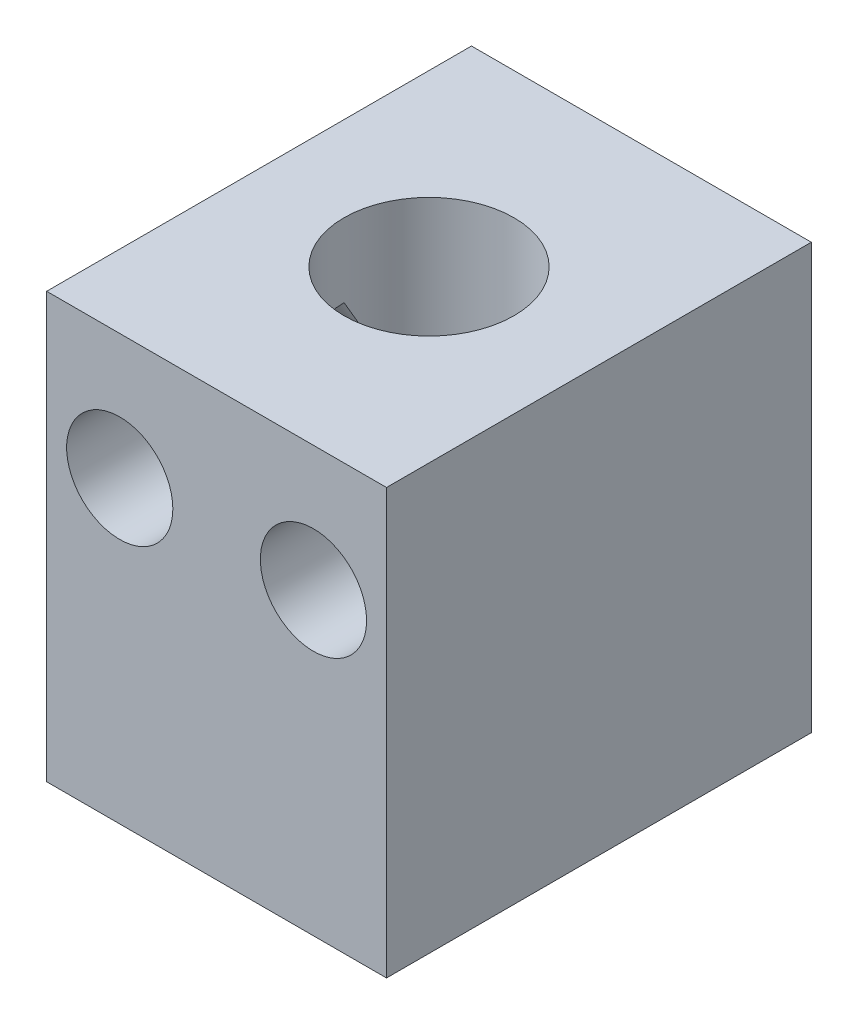
SolidWorks part; units mm, degrees
ref_plane "Plan de face" through (0, 0, 0) normal (0, 0, 1) x (1, 0, 0)
ref_plane "Plan de dessus" through (0, 0, 0) normal (0, 1, 0) x (1, 0, 0)
ref_plane "Plan de droite" through (0, 0, 0) normal (1, 0, 0) x (0, 0, -1)
sketch "Esquisse1" plane through (0, 0, 0) normal (0, 1, 0) x (1, 0, 0)
  line L1 (-4, -5) -> (4, -5)
  line L2 (-4, -5) -> (-4, 5)
  line L3 (-4, 5) -> (4, 5)
  line L4 (4, -5) -> (4, 5)
  line L5 (-4, -5) -> (4, 5) construction
  line L6 (-4, 5) -> (4, -5) construction
  circle A0 centre (0, 0) radius 2
  point P0 (0, 0)
  dimension "D1" = 4
  dimension "D2" = 10
  dimension "D3" = 8
extrude "Boss.-Extru.1" add sketch "Esquisse1" along normal blind 10
hole_wizard "Trou taraudé M31" positions "Esquisse2" profile "Esquisse3" tap size "M3" standard "ISO"
sketch "Esquisse2" plane through (0, 0, 5) normal (0, 0, 1) x (1, 0, 0)
  line L0 (0, 10) -> (-2.2802, 7.0497) construction
  line L1 (-4, 10) -> (4, 10) construction
  line L2 (-2.2802, 7.0497) -> (2.2802, 7.0497) construction
  line L3 (2.2802, 7.0497) -> (0, 10) construction
  point P0 (-2.2802, 7.0497)
  point P2 (2.2802, 7.0497)
sketch "Esquisse3" plane through (-2.2802, 7.0497, 5) normal (1, 0, 0) x (0, -1, 0)
  line L0 (0, 0) -> (0, 5.7511)
  line L1 (0, 5.7511) -> (1.25, 5)
  line L2 (1.25, 5) -> (1.25, 0)
  line L5 (1.25, 0) -> (0, 0)
  line L10 (0, 5.7511) -> (-1.25, 5) construction
  line L11 (0, -6.35) -> (0, 107.95) construction
  dimension "Diamètre du trou pour taraudage" = 2.5
  dimension "Profondeur du trou pour taraudage" = 5
  dimension "Angle de pointe" = 118
cosmetic thread "Filetage de perçage1" parameters "D1"=5, "D2"=3
cosmetic thread "Filetage de perçage2" parameters "D1"=5, "D2"=3
